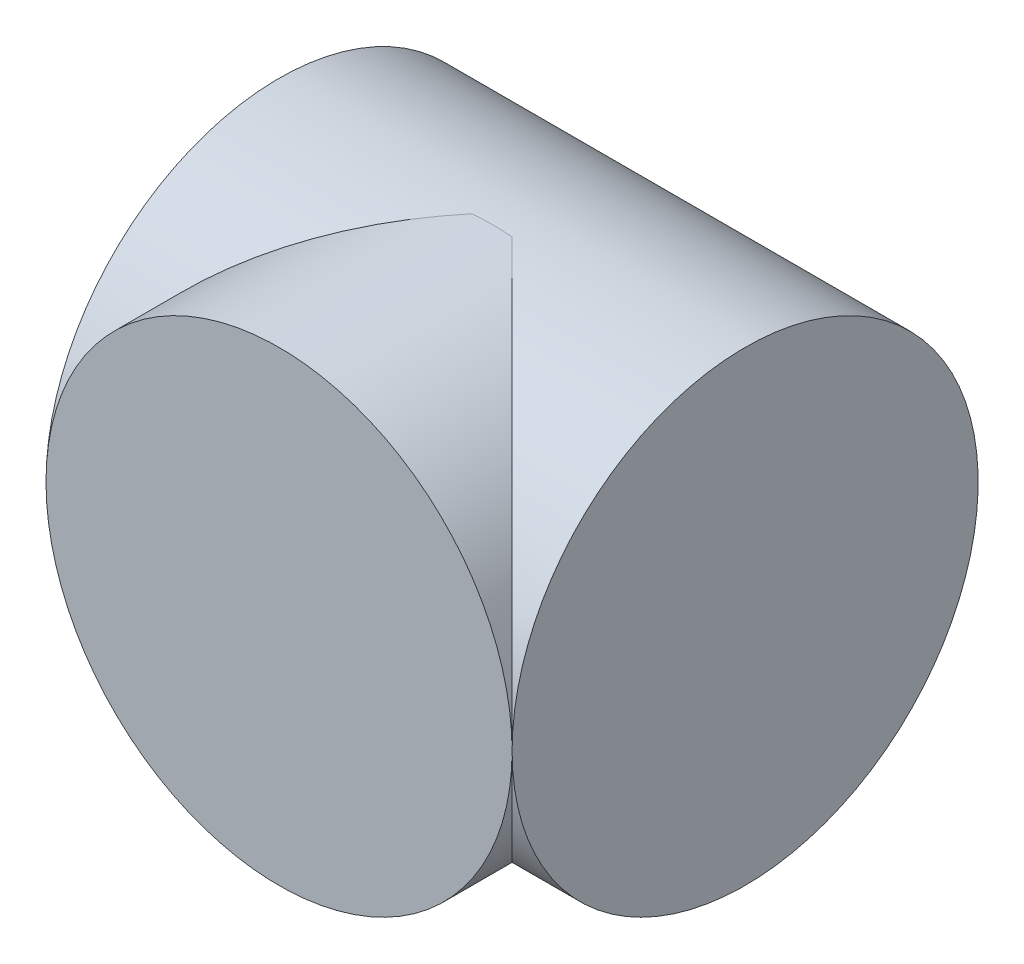
SolidWorks part; units mm, degrees
ref_plane "前视基准面" through (0, 0, 0) normal (0, 0, 1) x (1, 0, 0)
ref_plane "上视基准面" through (0, 0, 0) normal (0, 1, 0) x (1, 0, 0)
ref_plane "右视基准面" through (0, 0, 0) normal (1, 0, 0) x (0, 0, -1)
other "Configuration Table"
sketch "草图1" plane through (0, 0, 0) normal (1, 0, 0) x (0, 0, -1)
  circle A0 centre (0, 0) radius 35
  dimension "D1" = 70
extrude "凸台-拉伸1" add sketch "草图1" along normal blind 70
ref_plane "基准面1" through (0, 0, 35) normal (0, 0, 1) x (1, 0, 0)
sketch "草图2" plane through (0, 0, 35) normal (0, 0, 1) x (1, 0, 0)
  line L0 (0, 35) -> (70, 35)
  line L1 (0, 35) -> (0, -35) construction
  line L2 (70, -35) -> (70, 35) construction
  line L3 (70, 35) -> (70, -35)
  circle A0 centre (35, 0) radius 35
extrude "凸台-拉伸2" add sketch "草图2" against normal blind 32 contours A0
sketch "草图3" plane through (70, 0, 0) normal (1, 0, 0) x (0, 0, -1)
  circle A0 centre (0, 0) radius 35
